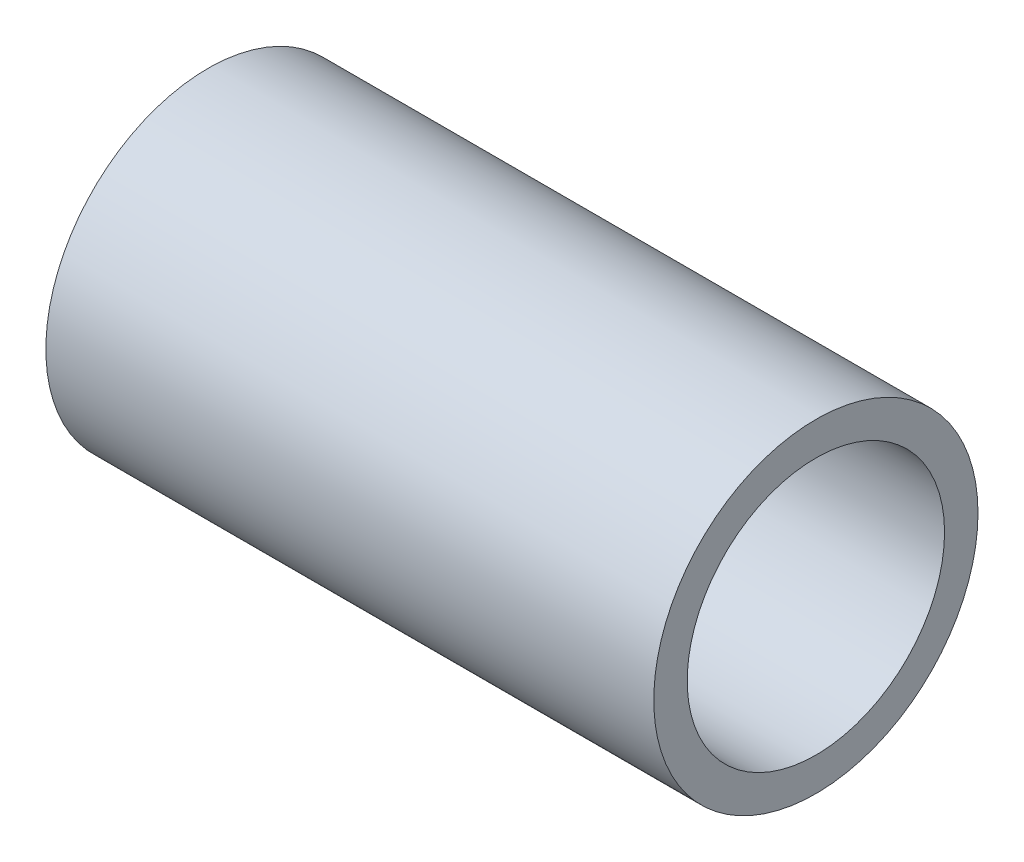
SolidWorks part; units mm, degrees
ref_plane "Front" through (0, 0, 0) normal (0, 0, 1) x (1, 0, 0)
ref_plane "Top" through (0, 0, 0) normal (0, 1, 0) x (1, 0, 0)
ref_plane "Right" through (0, 0, 0) normal (1, 0, 0) x (0, 0, -1)
sketch "Sketch1" plane through (0, 0, 0) normal (1, 0, 0) x (0, 0, -1)
  circle A0 centre (0, 0) radius 1.5875
  circle A1 centre (0, 0) radius 2
extrude "Boss-Extrude1" add sketch "Sketch1" along normal blind 7.5
